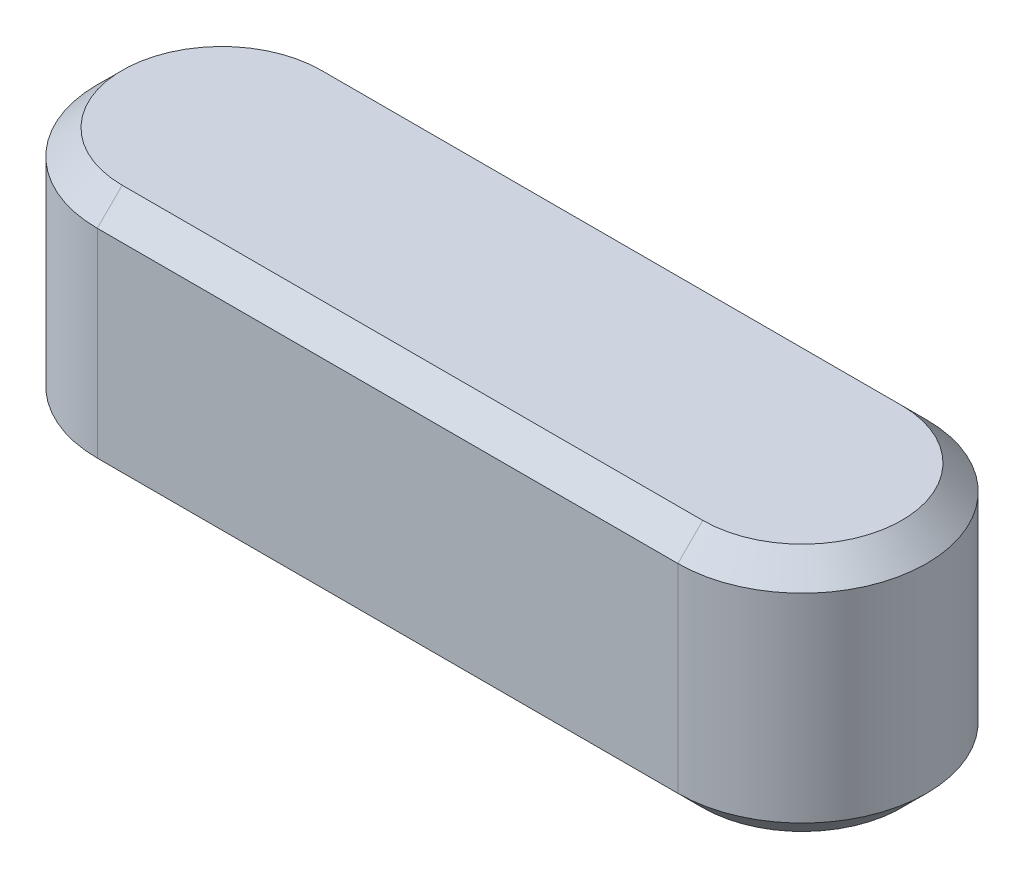
SolidWorks part; units mm, degrees
material "AISI 304"
ref_plane "前视基准面" through (0, 0, 0) normal (0, 0, 1) x (1, 0, 0)
ref_plane "上视基准面" through (0, 0, 0) normal (0, 1, 0) x (1, 0, 0)
ref_plane "右视基准面" through (0, 0, 0) normal (1, 0, 0) x (0, 0, -1)
sketch "草图1" plane through (0, 0, 0) normal (0, 1, 0) x (1, 0, 0)
  line L0 (-3.5, 0) -> (3.5, 0) construction
  line L1 (-3.5, 1.5) -> (3.5, 1.5)
  line L2 (-3.5, -1.5) -> (3.5, -1.5)
  arc A0 (-3.5, 1.5) -> (-3.5, -1.5) centre (-3.5, 0) ccw
  arc A1 (3.5, -1.5) -> (3.5, 1.5) centre (3.5, 0) ccw
  point P2 (0, 0)
  dimension "宽" = 3
  dimension "长" = 10
extrude "凸台-拉伸1" add sketch "草图1" along normal blind 3
chamfer "倒角1" distance 0.3 angle 45 8 edges at (0, 3, -1.5) (-5, 3, 0) (5, 3, 0) (0, 3, 1.5) (0, 0, -1.5) (-5, 0, 0) (5, 0, 0) (0, 0, 1.5)
